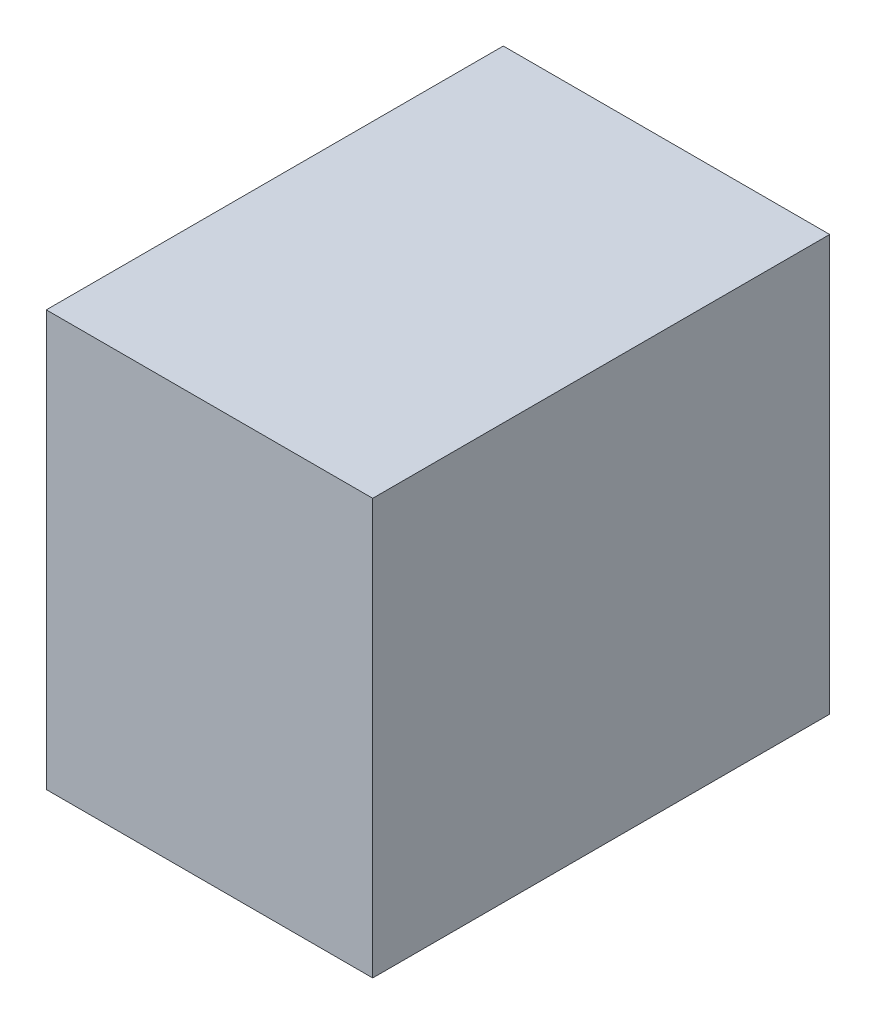
SolidWorks part; units mm, degrees
ref_plane "Front Plane" through (0, 0, 0) normal (0, 0, 1) x (1, 0, 0)
ref_plane "Top Plane" through (0, 0, 0) normal (0, 1, 0) x (1, 0, 0)
ref_plane "Right Plane" through (0, 0, 0) normal (1, 0, 0) x (0, 0, -1)
sketch "Sketch1" plane through (0, 0, 0) normal (1, 0, 0) x (0, 0, -1)
  line L1 (-38.5, 35) -> (38.5, 35)
  line L2 (-38.5, 35) -> (-38.5, -35)
  line L3 (-38.5, -35) -> (38.5, -35)
  line L4 (38.5, 35) -> (38.5, -35)
  line L5 (-38.5, 35) -> (38.5, -35) construction
  line L6 (-38.5, -35) -> (38.5, 35) construction
  point P0 (0, 0)
  dimension "D1" = 77
  dimension "D2" = 70
extrude "Boss-Extrude1" add sketch "Sketch1" along normal blind 55
ref_plane "Plane1" through (0, 0, 28.5) normal (0, 0, 1) x (1, 0, 0)
sketch "Sketch3" plane through (0, 0, 28.5) normal (0, 0, 1) x (1, 0, 0)
  line L1 (10, 25) -> (45, 25)
  line L2 (10, 25) -> (10, -25)
  line L3 (10, -25) -> (45, -25)
  line L4 (45, 25) -> (45, -25)
  line L6 (55, 35) -> (0, 35) construction
  line L7 (0, 35) -> (0, -35) construction
  dimension "D1" = 35
  dimension "D2" = 50
  dimension "D3" = 10
  dimension "D4" = 10
extrude "Cut-Extrude1" cut sketch "Sketch3" against normal blind 57
